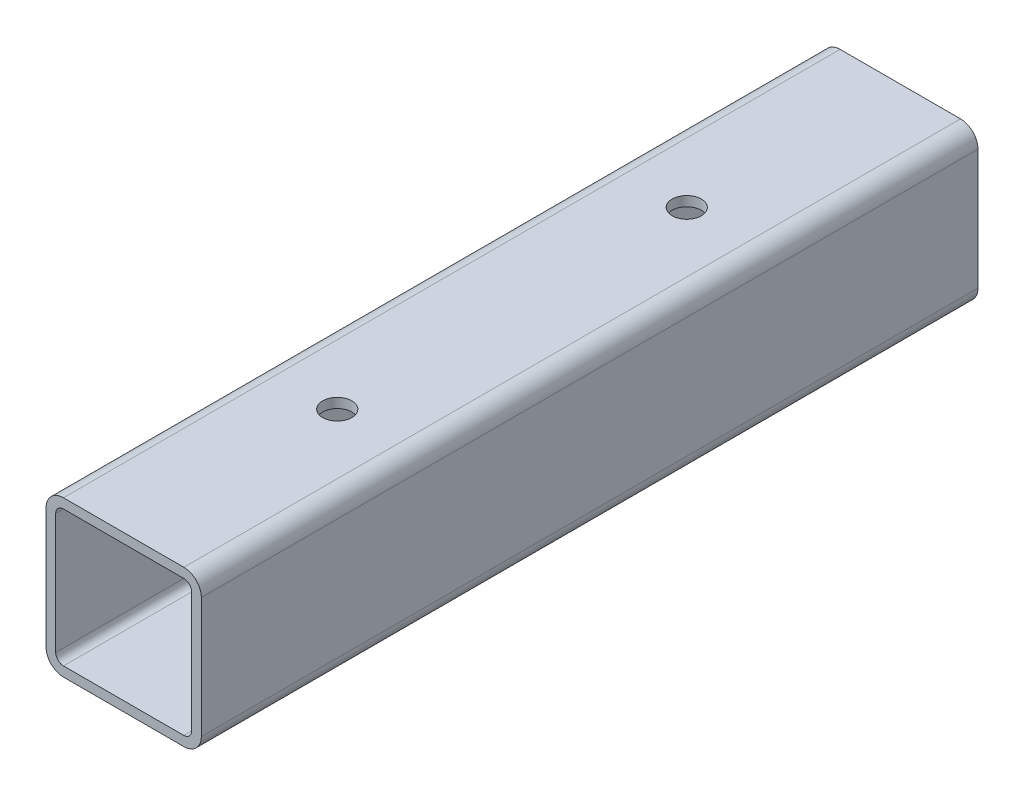
SolidWorks part; units mm, degrees
ref_plane "Front Plane" through (0, 0, 0) normal (0, 0, 1) x (1, 0, 0)
ref_plane "Top Plane" through (0, 0, 0) normal (0, 1, 0) x (1, 0, 0)
ref_plane "Right Plane" through (0, 0, 0) normal (1, 0, 0) x (0, 0, -1)
sketch "Sketch1" plane through (0, 0, 0) normal (0, 0, 1) x (1, 0, 0)
  line L0 (-95.0336, 0) -> (95.0336, 0) construction
  line L1 (0, -87.7187) -> (0, 87.7187) construction
  line L2 (-19.685, 25.4) -> (19.685, 25.4)
  line L3 (-19.685, -22.225) -> (19.685, -22.225)
  line L4 (-22.225, -19.685) -> (-22.225, 19.685)
  line L5 (-19.685, 22.225) -> (19.685, 22.225)
  line L6 (22.225, -19.685) -> (22.225, 19.685)
  line L7 (-22.225, -22.225) -> (22.225, 22.225) construction
  line L8 (-22.225, 22.225) -> (22.225, -22.225) construction
  line L9 (25.4, -19.685) -> (25.4, 19.685)
  line L10 (-19.685, -25.4) -> (19.685, -25.4)
  line L11 (-25.4, -19.685) -> (-25.4, 19.685)
  arc A0 (-19.685, -22.225) -> (-22.225, -19.685) centre (-19.685, -19.685) cw
  arc A1 (19.685, -22.225) -> (22.225, -19.685) centre (19.685, -19.685) ccw
  arc A2 (19.685, 22.225) -> (22.225, 19.685) centre (19.685, 19.685) cw
  arc A3 (-22.225, 19.685) -> (-19.685, 22.225) centre (-19.685, 19.685) cw
  arc A4 (19.685, 25.4) -> (25.4, 19.685) centre (19.685, 19.685) cw
  arc A5 (19.685, -25.4) -> (25.4, -19.685) centre (19.685, -19.685) ccw
  arc A6 (-19.685, -25.4) -> (-25.4, -19.685) centre (-19.685, -19.685) cw
  arc A7 (-25.4, 19.685) -> (-19.685, 25.4) centre (-19.685, 19.685) cw
  point P0 (0, 0)
  point P4 (0, 0)
  point P8 (0, 0)
  dimension "D3" = 2.54
  dimension "D1" = 44.45
  dimension "D2" = 44.45
  dimension "D4" = 3.175
extrude "Boss-Extrude1" add sketch "Sketch1" along normal mid plane 254
sketch "Sketch2" plane through (0, 0, 0) normal (0, 1, 0) x (1, 0, 0)
  line L0 (-99.3413, 0) -> (99.3413, 0) construction
  line L1 (0, 129.9829) -> (0, -129.9829) construction
  circle A0 centre (0, 57.15) radius 4.7625
  circle A1 centre (0, -57.15) radius 4.7625
  point P4 (0, 0)
  point P8 (0, 0)
  dimension "D1" = 9.525
  dimension "D2" = 57.15
extrude "Cut-Extrude1" cut sketch "Sketch2" against normal mid plane 76.2
